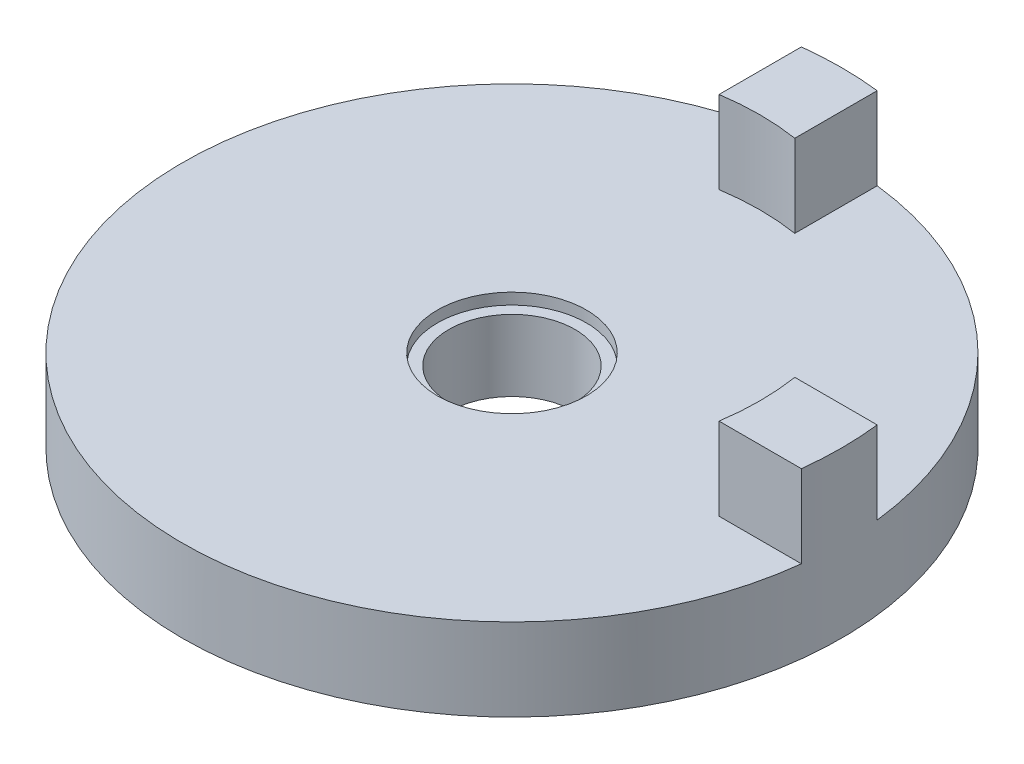
SolidWorks part; units mm, degrees
ref_plane "Front Plane" through (0, 0, 0) normal (0, 0, 1) x (1, 0, 0)
ref_plane "Top Plane" through (0, 0, 0) normal (0, 1, 0) x (1, 0, 0)
ref_plane "Right Plane" through (0, 0, 0) normal (1, 0, 0) x (0, 0, -1)
sketch "Sketch1" plane through (0, 0, 0) normal (0, 1, 0) x (1, 0, 0)
  circle A0 centre (0, 0) radius 25.4
  dimension "D1" = 50.8
extrude "Boss-Extrude1" add sketch "Sketch1" along normal blind 6.35
sketch "Sketch2" plane through (0, 6.35, 0) normal (0, 1, 0) x (1, 0, 0)
  circle A0 centre (0, 0) radius 4.8641
  dimension "D1" = 9.7282
extrude "Cut-Extrude1" cut sketch "Sketch2" against normal through all
sketch "Sketch3" plane through (0, 6.35, 0) normal (0, 1, 0) x (1, 0, 0)
  circle A0 centre (0, 0) radius 5.7404
  dimension "D1" = 11.4808
extrude "Cut-Extrude3" cut sketch "Sketch3" against normal blind 0.8636
sketch "Sketch4" plane through (0, 6.35, 0) normal (0, 1, 0) x (1, 0, 0)
  line L0 (0, 0) -> (0, 25.4) construction
  line L1 (25.4, 0) -> (-25.4, 0) construction
  line L2 (18.8815, 2.921) -> (25.2315, 2.921)
  line L3 (18.8815, -2.921) -> (25.2315, -2.921)
  line L4 (-2.921, 18.8815) -> (-2.921, 25.2315)
  line L5 (18.8815, 2.921) -> (25.2315, -2.921) construction
  line L6 (2.921, 18.8815) -> (2.921, 25.2315)
  line L7 (-2.921, 18.8815) -> (2.921, 25.2315) construction
  line L8 (25.2315, 2.921) -> (18.8815, -2.921) construction
  line L9 (0, 0) -> (2.921, 18.8815) construction
  line L10 (0, 0) -> (18.8815, -2.921) construction
  line L13 (-2.921, 25.2315) -> (2.921, 18.8815) construction
  circle A0 centre (0, 0) radius 25.4 construction
  arc A1 (2.921, 25.2315) -> (-2.921, 25.2315) centre (0, 0) ccw
  arc A2 (25.2315, -2.921) -> (25.2315, 2.921) centre (0, 0) ccw
  arc A3 (2.921, 18.8815) -> (-2.921, 18.8815) centre (0, 0) ccw
  arc A4 (18.8815, -2.921) -> (18.8815, 2.921) centre (0, 0) ccw
  point P6 (0, 22.0565)
  point P16 (22.0565, 0)
  circle M2 centre (0, 0) radius 25.4
  dimension "D1" = 5.842
  dimension "D2" = 6.35
  dimension "D4" = 90
  dimension "D3" = 2
extrude "Boss-Extrude2" add sketch "Sketch4" along normal blind 6.35 contours A3 L6 L4 M2 | A4 L3 L2 M2
